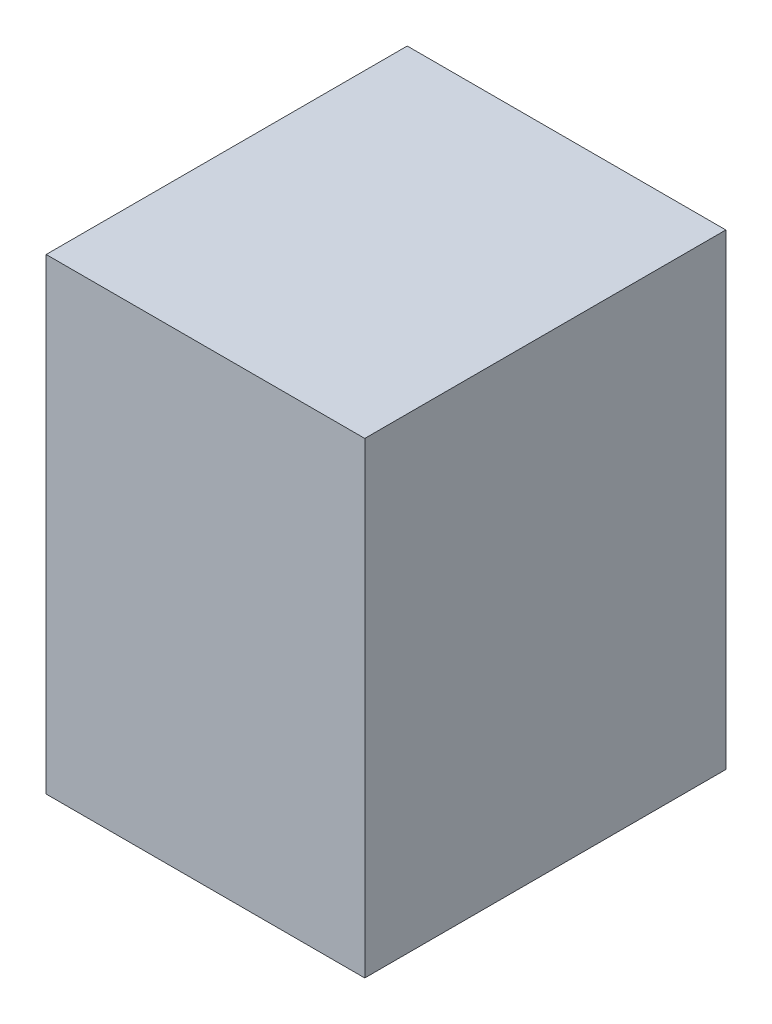
SolidWorks part; units mm, degrees
ref_plane "Front Plane" through (0, 0, 0) normal (0, 0, 1) x (1, 0, 0)
ref_plane "Top Plane" through (0, 0, 0) normal (0, 1, 0) x (1, 0, 0)
ref_plane "Right Plane" through (0, 0, 0) normal (1, 0, 0) x (0, 0, -1)
sketch "Sketch1" plane through (0, 0, 0) normal (1, 0, 0) x (0, 0, -1)
  line L1 (-14.6419, 55.88) -> (28.5381, 55.88)
  line L2 (-14.6419, 55.88) -> (-14.6419, 0)
  line L3 (-14.6419, 0) -> (28.5381, 0)
  line L4 (28.5381, 55.88) -> (28.5381, 0)
  dimension "D1" = 55.88
  dimension "D2" = 43.18
extrude "Boss-Extrude1" add sketch "Sketch1" along normal blind 38.1
sketch "Sketch2" plane through (0, 0, 0) normal (-1, 0, 0) x (0, 0, 1)
  line L0 (14.6419, 0) -> (-28.5381, 0) construction
  line L1 (-25.9981, 5.08) -> (12.1019, 5.08)
  line L2 (-25.9981, 5.08) -> (-25.9981, 50.8)
  line L3 (-25.9981, 50.8) -> (12.1019, 50.8)
  line L4 (12.1019, 5.08) -> (12.1019, 50.8)
  line L5 (-28.5381, 0) -> (-28.5381, 55.88) construction
  line L6 (14.6419, 55.88) -> (14.6419, 0) construction
  circle A0 centre (-17.9608, 10.16) radius 2.54
  circle A1 centre (-17.9608, 45.72) radius 2.54
  circle A2 centre (-17.9608, 27.94) radius 3.429
  circle A3 centre (-7.8008, 27.94) radius 2.54
  dimension "D6" = 5.08
  dimension "D7" = 5.08
  dimension "D8" = 6.858
  dimension "D9" = 5.08
  dimension "D1" = 10.16
  dimension "D2" = 17.78
  dimension "D3" = 17.78
  dimension "D4" = 27.94
  dimension "D5" = 45.72
  dimension "D10" = 5.08
  dimension "D11" = 2.54
  dimension "D12" = 2.54
  dimension "D13" = 19.9027
  dimension "D14" = 5.08
  dimension "D15" = 17.78
